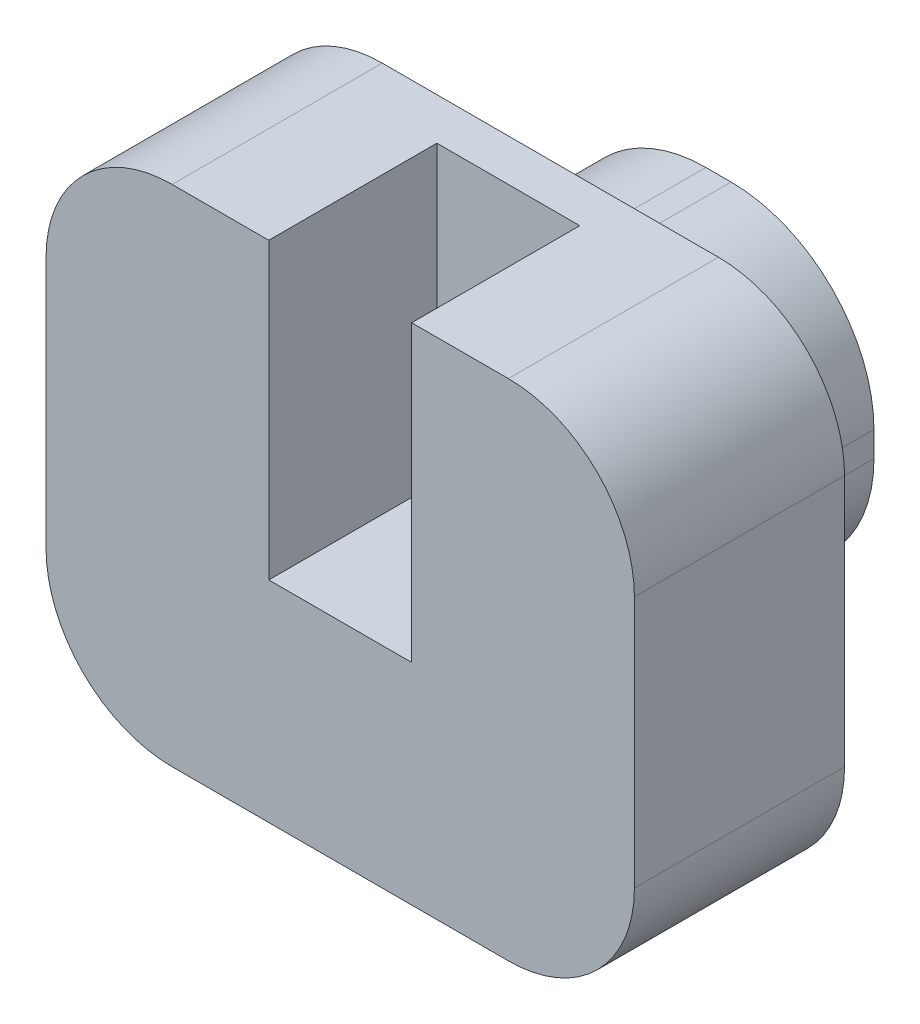
SolidWorks part; units mm, degrees
ref_plane "Спереди" through (0, 0, 0) normal (0, 0, 1) x (1, 0, 0)
ref_plane "Сверху" through (0, 0, 0) normal (0, 1, 0) x (1, 0, 0)
ref_plane "Справа" through (0, 0, 0) normal (1, 0, 0) x (0, 0, -1)
sketch "Эскиз1" plane through (0, 0, 0) normal (0, 0, 1) x (1, 0, 0)
  line L1 (-0.15, -1.85) -> (0.15, -1.85)
  line L2 (-1.85, -0.15) -> (-1.85, 0.15)
  line L3 (-0.15, 1.85) -> (0.15, 1.85)
  line L4 (1.85, -0.15) -> (1.85, 0.15)
  line L5 (-1.85, -1.85) -> (1.85, 1.85) construction
  line L6 (-1.85, 1.85) -> (1.85, -1.85) construction
  arc A0 (-1.85, -0.15) -> (-0.15, -1.85) centre (-0.15, -0.15) ccw
  arc A1 (1.85, 0.15) -> (0.15, 1.85) centre (0.15, 0.15) ccw
  arc A2 (-0.15, 1.85) -> (-1.85, 0.15) centre (-0.15, 0.15) ccw
  arc A3 (1.85, -0.15) -> (0.15, -1.85) centre (0.15, -0.15) cw
  point P0 (0, 0)
  dimension "D3" = 1.7
  dimension "D1" = 3.7
  dimension "D2" = 3.7
extrude "Бобышка-Вытянуть1" add sketch "Эскиз1" along normal blind 2
sketch "Эскиз2" plane through (0, 0, 2) normal (0, 0, 1) x (1, 0, 0)
  line L1 (-2, -3) -> (2, -3)
  line L2 (-3.5, -1.5) -> (-3.5, 1.5)
  line L3 (-2, 3) -> (2, 3)
  line L4 (3.5, -1.5) -> (3.5, 1.5)
  line L5 (-3.5, -3) -> (3.5, 3) construction
  line L6 (-3.5, 3) -> (3.5, -3) construction
  arc A0 (2, -3) -> (3.5, -1.5) centre (2, -1.5) ccw
  arc A1 (-2, -3) -> (-3.5, -1.5) centre (-2, -1.5) cw
  arc A2 (3.5, 1.5) -> (2, 3) centre (2, 1.5) ccw
  arc A3 (-3.5, 1.5) -> (-2, 3) centre (-2, 1.5) cw
  point P0 (0, 0)
  dimension "D3" = 1.5
  dimension "D1" = 7
  dimension "D2" = 6
extrude "Бобышка-Вытянуть2" add sketch "Эскиз2" along normal blind 2.5 contours A3 L2 A1 L1 A0 L4 A2 L3
sketch "Эскиз4" plane through (0, 3, 0) normal (0, 1, 0) x (1, 0, 0)
  line L0 (3.5, -4.5) -> (3.5, -2) construction
  line L1 (-2, -4.5) -> (2, -4.5) construction
  line L2 (-0.85, -4.5) -> (0.85, -4.5)
  line L3 (-0.85, -4.5) -> (-0.85, -2.5)
  line L4 (-0.85, -2.5) -> (0.85, -2.5)
  line L5 (0.85, -4.5) -> (0.85, -2.5)
  line L6 (-0.85, -4.5) -> (0.85, -2.5) construction
  line L7 (-0.85, -2.5) -> (0.85, -4.5) construction
  point P3 (0, -3.5)
  point P8 (0, -4.5)
  dimension "D1" = 2
  dimension "D2" = 1.7
  dimension "D3" = 3.5
extrude "Вырез-Вытянуть1" cut sketch "Эскиз4" against normal blind 3.5
equation "\"D3@Эскиз4\"=\"D1@Эскиз2\"/2"
